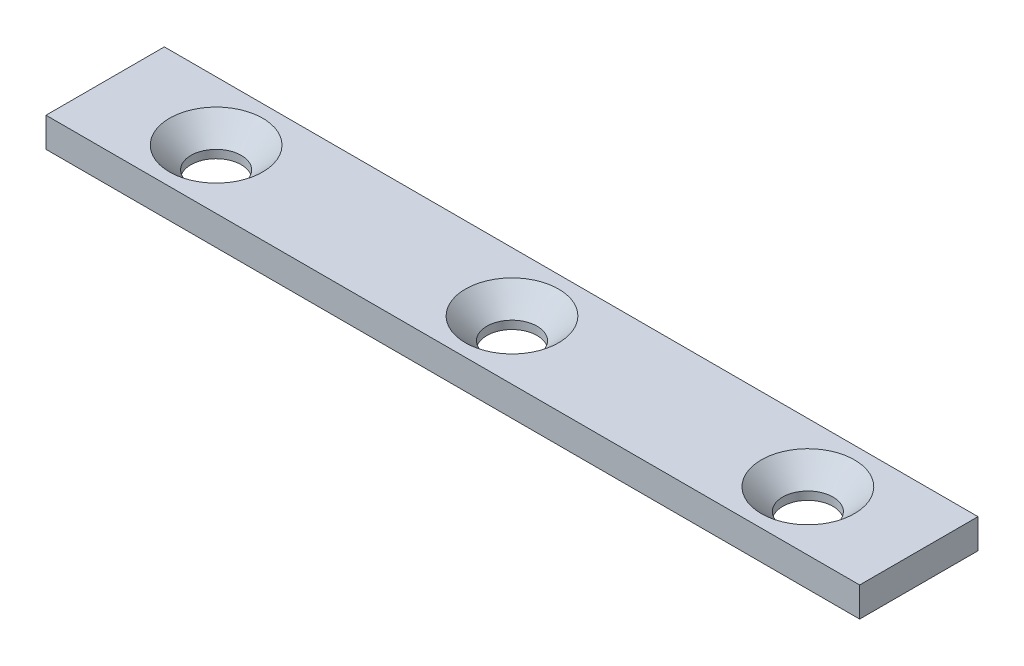
SolidWorks part; units mm, degrees
ref_plane "Front Plane" through (0, 0, 0) normal (0, 0, 1) x (1, 0, 0)
ref_plane "Top Plane" through (0, 0, 0) normal (0, 1, 0) x (1, 0, 0)
ref_plane "Right Plane" through (0, 0, 0) normal (1, 0, 0) x (0, 0, -1)
sketch "Sketch1" plane through (0, 0, 0) normal (0, 1, 0) x (1, 0, 0)
  line L1 (27.5, -4) -> (-27.5, -4)
  line L2 (27.5, -4) -> (27.5, 4)
  line L3 (27.5, 4) -> (-27.5, 4)
  line L4 (-27.5, -4) -> (-27.5, 4)
  line L5 (27.5, -4) -> (-27.5, 4) construction
  line L6 (27.5, 4) -> (-27.5, -4) construction
  point P0 (0, 0)
  dimension "D1" = 8
  dimension "D2" = 55
extrude "Boss-Extrude1" add sketch "Sketch1" along normal blind 2
sketch "Sketch2" plane through (0, 2, 0) normal (0, 1, 0) x (1, 0, 0)
  line L0 (0, 0) -> (-20, 0) construction
  dimension "D1" = 20
hole_wizard "CSK for M3 Countersunk Flat Head1" positions "3DSketch1" profile "Sketch3" countersink size "M3" standard "BSI" end condition through all
sketch3d "3DSketch1"
  point P0 (-20, 2, 0)
sketch "Sketch3" plane through (-20, 2, 0) normal (1, 0, 0) x (0, 0, 1)
  line L0 (0, 0) -> (0, 2)
  line L1 (0, 2) -> (1.7, 2)
  line L2 (1.7, 2) -> (1.7, 1.45)
  line L3 (1.7, 1.45) -> (3.15, 0)
  line L5 (3.15, 0) -> (0, 0)
  line L6 (-1.7, 1.45) -> (-3.15, 0) construction
  line L11 (0, -6.35) -> (0, 107.95) construction
  dimension "Thru Hole Dia." = 3.4
  dimension "Thru Hole Depth" = 2
  dimension "Near C'Sink Dia." = 6.3
  dimension "Near C'Sink Angle" = 90
pattern_linear "LPattern1" count 3 spacing 20 along (1, 0, 0) of "CSK for M3 Countersunk Flat Head1"
